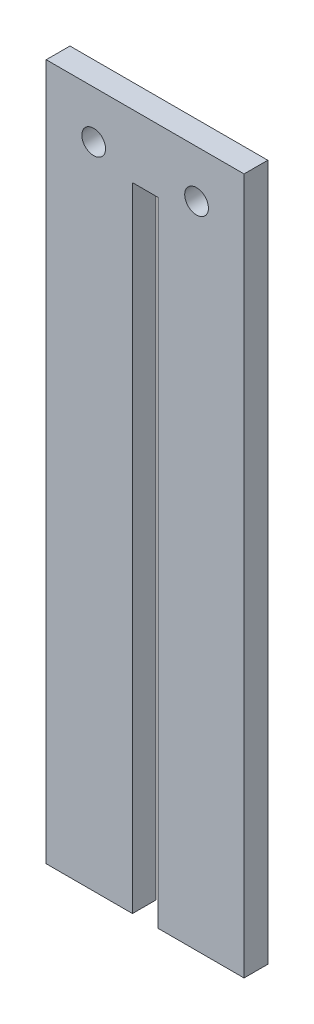
SolidWorks part; units mm, degrees
ref_plane "Front Plane" through (0, 0, 0) normal (0, 0, 1) x (1, 0, 0)
ref_plane "Top Plane" through (0, 0, 0) normal (0, 1, 0) x (1, 0, 0)
ref_plane "Right Plane" through (0, 0, 0) normal (1, 0, 0) x (0, 0, -1)
sketch "Sketch1" plane through (0, 0, 0) normal (0, 0, 1) x (1, 0, 0)
  line L1 (0, 0) -> (25, 0)
  line L2 (0, 0) -> (0, 88)
  line L3 (0, 88) -> (25, 88)
  line L4 (25, 0) -> (25, 88)
  dimension "D1" = 25
  dimension "D2" = 88
extrude "Boss-Extrude1" add sketch "Sketch1" along normal blind 3
sketch "Sketch2" plane through (0, 0, 3) normal (0, 0, 1) x (1, 0, 0)
  line L0 (25, 0) -> (25, 88) construction
  line L1 (25, 88) -> (0, 88) construction
  line L2 (0, 88) -> (0, 0) construction
  circle A0 centre (19, 82) radius 1.5
  circle A1 centre (6, 82) radius 1.5
  point P10 (0, 0)
  dimension "D1" = 6
  dimension "D2" = 3
  dimension "D3" = 6
  dimension "D4" = 3
  dimension "D5" = 6
extrude "Cut-Extrude1" cut sketch "Sketch2" against normal blind 3
sketch "Sketch3" plane through (0, 0, 3) normal (0, 0, 1) x (1, 0, 0)
  line L0 (14.1, 0) -> (14.1, 80)
  line L1 (0, 0) -> (25, 0) construction
  line L2 (14.1, 80) -> (10.9, 80)
  line L3 (10.9, 80) -> (10.9, 0)
  line L4 (25, 88) -> (0, 88) construction
  line L5 (10.9, 0) -> (0, 0) construction
  line L6 (14.1, 0) -> (25, 0) construction
  line L7 (14.1, 0) -> (10.9, 0)
  dimension "D1" = 8
  dimension "D2" = 3.2
extrude "Cut-Extrude2" cut sketch "Sketch3" against normal blind 10
